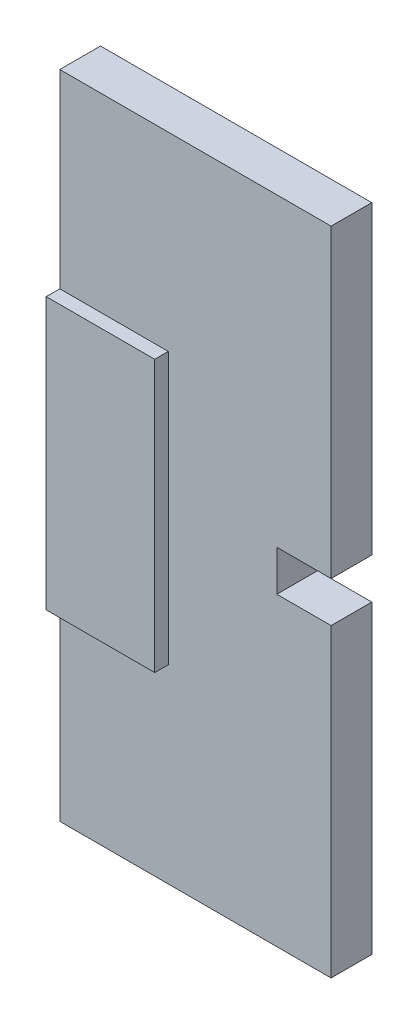
SolidWorks part; units mm, degrees
material "Polyurethane Foam Flexible"
ref_plane "Front Plane" through (0, 0, 0) normal (0, 0, 1) x (1, 0, 0)
ref_plane "Top Plane" through (0, 0, 0) normal (0, 1, 0) x (1, 0, 0)
ref_plane "Right Plane" through (0, 0, 0) normal (1, 0, 0) x (0, 0, -1)
sketch "Sketch1" plane through (0, 0, 0) normal (0, 0, 1) x (1, 0, 0)
  line L1 (5.6951, 15.4336) -> (43.7951, 15.4336)
  line L2 (5.6951, 15.4336) -> (5.6951, -60.7664)
  line L3 (5.6951, -60.7664) -> (43.7951, -60.7664)
  line L4 (43.7951, 15.4336) -> (43.7951, -60.7664)
  line L5 (43.7951, -22.6664) -> (43.7951, -20.2851)
  line L6 (43.7951, -20.2851) -> (31.0951, -20.2851)
  line L7 (31.0951, -20.2851) -> (31.0951, -25.0476)
  line L8 (31.0951, -25.0476) -> (43.7951, -25.0476)
  line L9 (43.7951, -25.0476) -> (43.7951, -22.6664)
  dimension "D1" = 38.1
  dimension "D2" = 76.2
  dimension "D4" = 2.3813
  dimension "D5" = 2.3813
  dimension "D6" = 4.7625
extrude "Boss-Extrude3" add sketch "Sketch1" along normal blind 4.7625 contours L8 L7 L6 L4 L1 L2 L3
sketch "Sketch2" [suppressed] plane through (0, 0, 4.7625) normal (0, 0, 1) x (1, 0, 0)
  line L0 (43.7951, -16.3164) -> (31.0951, -16.3164) construction
  line L1 (43.7951, 15.4336) -> (37.4451, 15.4336)
  line L2 (43.7951, 15.4336) -> (43.7951, -16.3164)
  line L3 (43.7951, -16.3164) -> (37.4451, -16.3164)
  line L4 (37.4451, 15.4336) -> (37.4451, -16.3164)
  line L5 (-57.8049, -60.7664) -> (43.7951, -60.7664) construction
  line L6 (37.4451, -60.7664) -> (43.7951, -60.7664)
  line L7 (37.4451, -60.7664) -> (37.4451, -29.0164)
  line L8 (37.4451, -29.0164) -> (43.7951, -29.0164)
  line L9 (43.7951, -60.7664) -> (43.7951, -29.0164)
  line M9 (43.7951, -29.0164) -> (31.0951, -29.0164)
  line M15 (-57.8049, -60.7664) -> (43.7951, -60.7664)
  line M16 (43.7951, -60.7664) -> (43.7951, -29.0164)
extrude "Boss-Extrude4" [suppressed] add sketch "Sketch2" along normal blind 12.7 contours L7 M15 M16 M9 | L2 L1 L4 L3
sketch "Sketch3" plane through (0, 0, 4.7625) normal (0, 0, 1) x (1, 0, 0)
  line L0 (5.6951, 15.4336) -> (5.6951, -22.6664)
  line L1 (5.6951, 15.4336) -> (5.6951, -60.7664) construction
  line L2 (5.6951, -22.6664) -> (12.0451, -22.6664)
  line L4 (5.6951, -6.7914) -> (18.3951, -6.7914)
  line L5 (5.6951, -6.7914) -> (5.6951, -38.5414)
  line L6 (5.6951, -38.5414) -> (18.3951, -38.5414)
  line L7 (18.3951, -6.7914) -> (18.3951, -38.5414)
  line L8 (5.6951, -6.7914) -> (18.3951, -38.5414) construction
  line L9 (5.6951, -38.5414) -> (18.3951, -6.7914) construction
  dimension "D1" = 6.35
  dimension "D2" = 31.75
  dimension "D3" = 12.7
extrude "Boss-Extrude5" add sketch "Sketch3" along normal blind 1.5875
sketch "Sketch5" [suppressed] plane through (0, -60.7664, 0) normal (0, -1, 0) x (1, 0, 0)
  line L1 (43.7951, 0) -> (37.4451, 0)
  line L2 (43.7951, 0) -> (43.7951, 4.7625)
  line L4 (37.4451, 0) -> (37.4451, 4.7625)
sketch "Sketch6" [suppressed] plane through (0, -29.0164, 0) normal (0, 1, 0) x (1, 0, 0)
  line L1 (37.4451, -4.7625) -> (43.7951, -4.7625)
  line L2 (37.4451, -4.7625) -> (37.4451, 0)
  line L3 (37.4451, 0) -> (43.7951, 0)
  line L4 (43.7951, -4.7625) -> (43.7951, 0)
sketch "Sketch11" [suppressed] plane through (0, 0, 4.7625) normal (0, 0, 1) x (1, 0, 0)
  line L6 (-57.8049, -60.7664) -> (43.7951, -60.7664) construction
  line L7 (43.7951, -29.0164) -> (37.4451, -29.0164)
  line L8 (43.7951, -29.0164) -> (43.7951, -60.7664)
  line L9 (43.7951, -60.7664) -> (37.4451, -60.7664)
  line L10 (37.4451, -29.0164) -> (37.4451, -60.7664)
  dimension "D1" = 6.35
sketch "Sketch12" plane through (0, 0, 4.7625) normal (0, 0, 1) x (1, 0, 0)
  line L0 (31.0951, -25.0476) -> (43.7951, -25.0476) construction
  line L1 (43.7951, -60.7664) -> (37.4451, -60.7664)
  line L2 (43.7951, -60.7664) -> (43.7951, -25.0476)
  line L3 (43.7951, -25.0476) -> (37.4451, -25.0476)
  line L4 (37.4451, -60.7664) -> (37.4451, -25.0476)
  line L5 (5.6951, 15.4336) -> (43.7951, 15.4336) construction
  line L6 (43.7951, -20.2851) -> (37.4451, -20.2851)
  line L7 (43.7951, -20.2851) -> (43.7951, 15.4336)
  line L8 (43.7951, 15.4336) -> (37.4451, 15.4336)
  line L9 (37.4451, -20.2851) -> (37.4451, 15.4336)
  dimension "D1" = 6.35
  dimension "D2" = 6.35
extrude "Cut-Extrude1" cut sketch "Sketch12" against normal blind 9.652
